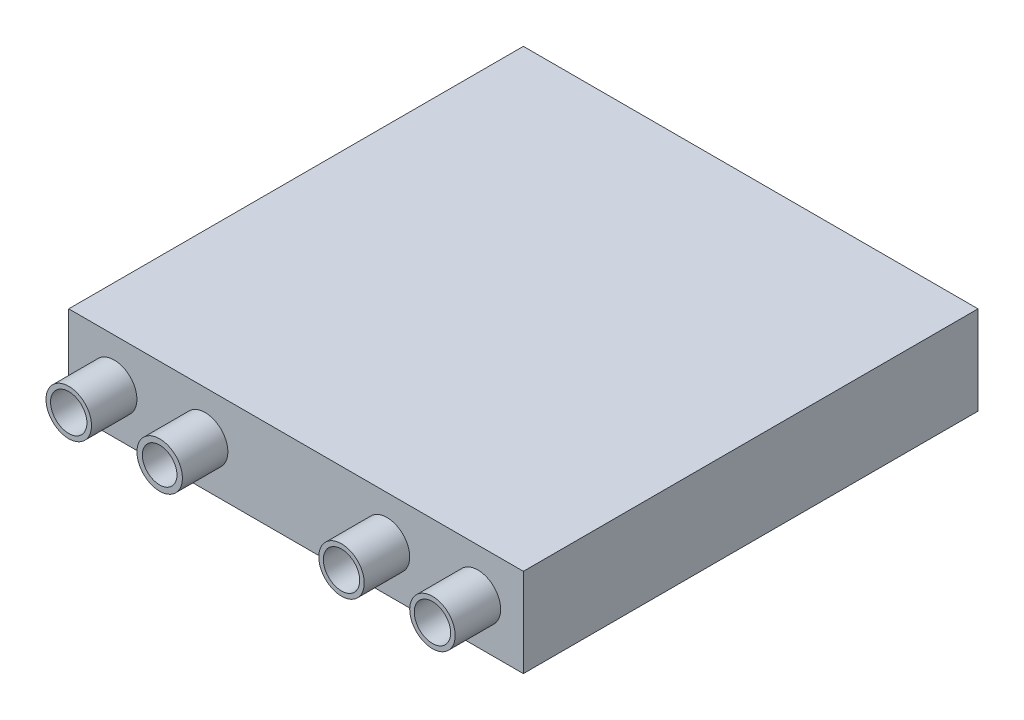
SolidWorks part; units mm, degrees
ref_plane "Front Plane" through (0, 0, 0) normal (0, 0, 1) x (1, 0, 0)
ref_plane "Top Plane" through (0, 0, 0) normal (0, 1, 0) x (1, 0, 0)
ref_plane "Right Plane" through (0, 0, 0) normal (1, 0, 0) x (0, 0, -1)
sketch "Sketch1" plane through (0, 0, 0) normal (0, 0, 1) x (1, 0, 0)
  line L1 (0, 0) -> (1000, 0)
  line L2 (0, 0) -> (0, -195)
  line L3 (0, -195) -> (1000, -195)
  line L4 (1000, 0) -> (1000, -195)
  dimension "D1" = 1000
  dimension "D2" = 195
extrude "Boss-Extrude1" add sketch "Sketch1" along normal blind 1000 contours L2 L1 L4 L3
sketch "Sketch2" plane through (0, 0, 1000) normal (0, 0, 1) x (1, 0, 0)
  line L0 (0, 0) -> (0, -195) construction
  line L1 (1000, 0) -> (1000, -195) construction
  line L2 (0, 0) -> (1000, 0) construction
  circle A0 centre (100, -97.5) radius 50
  circle A1 centre (300, -97.5) radius 50
  circle A2 centre (700, -97.5) radius 50
  circle A3 centre (900, -97.5) radius 50
  circle A4 centre (100, -97.5) radius 40
  circle A5 centre (300, -97.5) radius 38.0498
  circle A6 centre (700, -97.5) radius 40
  circle A7 centre (900, -97.5) radius 40
  dimension "D1" = 100
  dimension "D2" = 100
  dimension "D3" = 100
  dimension "D4" = 100
  dimension "D5" = 200
  dimension "D6" = 200
  dimension "D8" = 100
  dimension "D11" = 80
  dimension "D12" = 76.0995
  dimension "D13" = 80
  dimension "D14" = 80
  dimension "D7" = 100
  dimension "D9" = 97.5
  dimension "D10" = 97.5
extrude "Boss-Extrude2" add sketch "Sketch2" along normal blind 100
sketch "Sketch5" plane through (0, 0, 1000) normal (0, 0, 1) x (1, 0, 0)
  circle A0 centre (100, -97.5) radius 40
  circle A1 centre (300, -97.5) radius 38.0498
  circle A2 centre (700, -97.5) radius 40
  circle A3 centre (900, -97.5) radius 40
extrude "Cut-Extrude1" cut sketch "Sketch5" against normal blind 964
